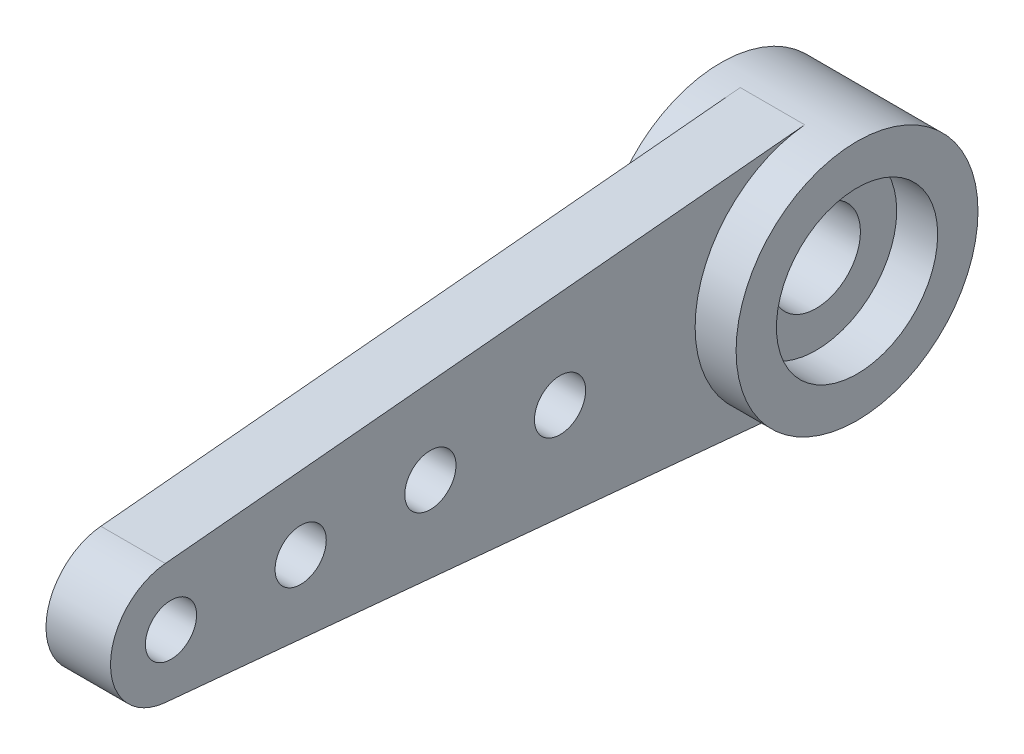
SolidWorks part; units mm, degrees
material "ABS"
ref_plane "Front Plane" through (0, 0, 0) normal (1, 0, 0) x (0, 1, 0)
ref_plane "Top Plane" through (0, 0, 0) normal (0, 0, 1) x (0, 1, 0)
ref_plane "Right Plane" through (0, 0, 0) normal (0, 1, 0) x (-1, 0, 0)
sketch "Sketch1" plane through (0, 0, 0) normal (1, 0, 0) x (0, 1, 0)
  line L0 (-2.9868, 0.2813) -> (-1.4934, 16.1406)
  line L1 (2.9868, 0.2813) -> (1.4934, 16.1406)
  line L2 (0, 16) -> (0, 0) construction
  circle A0 centre (0, 0) radius 1.1
  arc A1 (-2.9868, 0.2813) -> (2.9868, 0.2813) centre (0, 0) ccw
  arc A2 (-1.4934, 16.1406) -> (1.4934, 16.1406) centre (0, 16) cw
  circle A3 centre (0, 16) radius 0.635
  circle A7 centre (0, 12.7833) radius 0.635
  circle A8 centre (0, 9.5667) radius 0.635
  circle A9 centre (0, 6.35) radius 0.635
  dimension "D1" = 2.2
  dimension "D2" = 3
  dimension "D4" = 1.5
  dimension "D5" = 1.27
  dimension "D7" = 6.35
  dimension "D3" = 16
  dimension "D6" = 4
extrude "Boss-Extrude1" add sketch "Sketch1" along normal blind 1.6
sketch "Sketch2" plane through (1.6, 0, 0) normal (1, 0, 0) x (0, 1, 0)
  circle A0 centre (0, 0) radius 3
  circle A1 centre (0, 0) radius 2
  dimension "D1" = 6
  dimension "D2" = 4
extrude "Boss-Extrude2" add sketch "Sketch2" along normal blind 1.016
sketch "Sketch3" plane through (0, 0, 0) normal (-1, 0, 0) x (0, -1, 0)
  circle A0 centre (0, 0) radius 3
  circle A1 centre (0, 0) radius 2
  dimension "D1" = 4
  dimension "D2" = 6
extrude "Boss-Extrude3" add sketch "Sketch3" along normal blind 0.762
